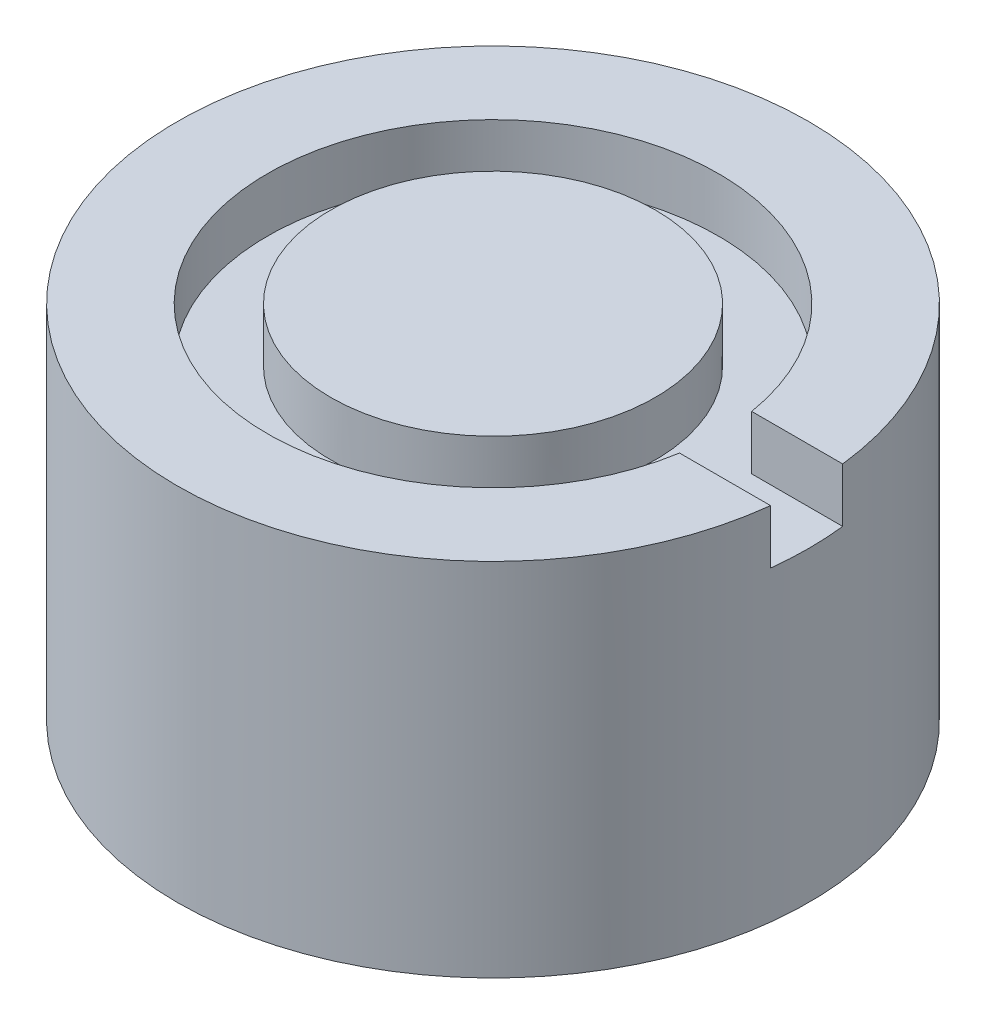
SolidWorks part; units mm, degrees
ref_plane "前视基准面" through (0, 0, 0) normal (0, 0, 1) x (1, 0, 0)
ref_plane "上视基准面" through (0, 0, 0) normal (0, 1, 0) x (1, 0, 0)
ref_plane "右视基准面" through (0, 0, 0) normal (1, 0, 0) x (0, 0, -1)
other "Configuration Table"
sketch "草图1" plane through (0, 0, 0) normal (0, 1, 0) x (1, 0, 0)
  circle A0 centre (0, 0) radius 3.05
  circle A1 centre (0, 0) radius 6
  dimension "D1" = 6.1
  dimension "D2" = 12
extrude "凸台-拉伸1" add sketch "草图1" along normal blind 9
sketch "草图2" plane through (0, 9, 0) normal (0, 1, 0) x (1, 0, 0)
  circle A0 centre (0, 0) radius 9
  dimension "D1" = 18
extrude "凸台-拉伸2" add sketch "草图2" along normal blind 3
sketch "草图3" plane through (0, 9, 0) normal (0, -1, 0) x (1, 0, 0)
  line L1 (-0.45, -4.3797) -> (0.45, -4.3797)
  line L2 (-0.45, -4.3797) -> (-0.45, 4.3797)
  line L3 (-0.45, 4.3797) -> (0.45, 4.3797)
  line L4 (0.45, -4.3797) -> (0.45, 4.3797)
  line L5 (-0.45, -4.3797) -> (0.45, 4.3797) construction
  line L6 (-0.45, 4.3797) -> (0.45, -4.3797) construction
  point P0 (0, 0)
  dimension "D1" = 0.9
extrude "凸台-拉伸3" add sketch "草图3" along normal blind 1
sketch "草图4" plane through (0, 9, 0) normal (0, -1, 0) x (1, 0, 0)
  circle A0 centre (0, 0) radius 6
  circle A1 centre (0, 0) radius 12.5
  dimension "D1" = 25
extrude "凸台-拉伸4" add sketch "草图4" along normal blind 10
sketch "草图5" plane through (0, -1, 0) normal (0, -1, 0) x (1, 0, 0)
  circle A0 centre (0, 0) radius 12.5
  circle A1 centre (0, 0) radius 11
  dimension "D1" = 22
extrude "凸台-拉伸5" add sketch "草图5" along normal blind 7
sketch "草图6" plane through (0, -8, 0) normal (0, -1, 0) x (1, 0, 0)
  circle A0 centre (0, 0) radius 12.5
  circle A1 centre (0, 0) radius 17.5
  dimension "D1" = 35
extrude "凸台-拉伸6" add sketch "草图6" against normal blind 20
sketch "草图7" plane through (0, 12, 0) normal (0, 1, 0) x (1, 0, 0)
  line L1 (11.8883, -2) -> (23.1117, -2)
  line L2 (11.8883, -2) -> (11.8883, 2)
  line L3 (11.8883, 2) -> (23.1117, 2)
  line L4 (23.1117, -2) -> (23.1117, 2)
  line L5 (11.8883, -2) -> (23.1117, 2) construction
  line L6 (11.8883, 2) -> (23.1117, -2) construction
  circle A0 centre (0, 0) radius 17.5 construction
  point P0 (17.5, 0)
  dimension "D1" = 4
extrude "切除-拉伸1" cut sketch "草图7" against normal blind 3
